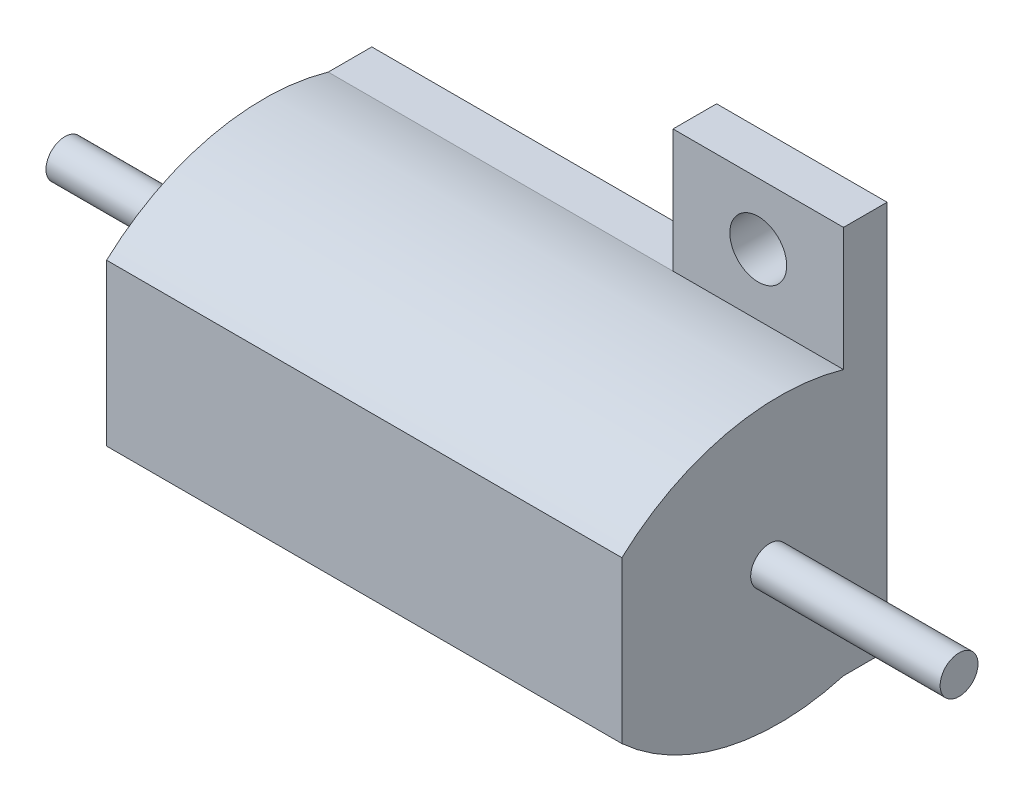
SolidWorks part; units mm, degrees
ref_plane "前视基准面" through (0, 0, 0) normal (0, 0, 1) x (1, 0, 0)
ref_plane "上视基准面" through (0, 0, 0) normal (0, 1, 0) x (1, 0, 0)
ref_plane "右视基准面" through (0, 0, 0) normal (1, 0, 0) x (0, 0, -1)
sketch "草图1" plane through (0, 0, 0) normal (0, 0, 1) x (1, 0, 0)
  line L0 (0, 21.2759) -> (0, -16.314) construction
  line L1 (-13.6, 7) -> (13.6, 7)
  line L2 (-13.6, 7) -> (-13.6, -7)
  line L3 (-13.6, -7) -> (13.6, -7)
  line L4 (13.6, 7) -> (13.6, -7)
  line L5 (-25.4038, 0) -> (20.5157, 0) construction
  dimension "D1" = 27.2
  dimension "D2" = 14
extrude "拉伸1" add sketch "草图1" along normal blind 2.3
sketch "草图2" plane through (0, 0, 0) normal (0, 0, -1) x (-1, 0, 0)
  line L0 (-9.1, 19.1659) -> (-9.1, 5.2783) construction
  line L1 (13.6, -7) -> (4.6, -7)
  line L2 (13.6, -7) -> (13.6, -13.5)
  line L3 (13.6, -13.5) -> (4.6, -13.5)
  line L4 (4.6, -7) -> (4.6, -13.5)
  line L5 (-13.6, 7) -> (-4.6, 7)
  line L6 (-13.6, 7) -> (-13.6, 13.5)
  line L7 (-13.6, 13.5) -> (-4.6, 13.5)
  line L8 (-4.6, 7) -> (-4.6, 13.5)
  line L9 (-1.9119, 10.25) -> (-15.2555, 10.25) construction
  line L10 (1.9413, -10.25) -> (18.3757, -10.25) construction
  line L11 (9.1, -6.7597) -> (9.1, -18.109) construction
  circle A0 centre (-9.1, 10.25) radius 1.5
  circle A1 centre (9.1, -10.25) radius 1.5
  dimension "D5" = 3
  dimension "D6" = 3
  dimension "D1" = 6.5
  dimension "D2" = 9
  dimension "D3" = 6.5
  dimension "D4" = 9
extrude "拉伸2" add sketch "草图2" against normal up to surface (2.3 mm away) up to face at (0, 0, 2.3)
sketch "草图4" plane through (13.6, 0, 0) normal (1, 0, 0) x (0, 0, -1)
  line L0 (-2.3, -7) -> (-2.3, 7)
  line L1 (8.3066, 0) -> (-17.5153, 0) construction
  line L2 (-14, -4.25) -> (-14, 4.25)
  line L3 (0, -7) -> (0, 13.5) construction
  arc A0 (-2.3, -7) -> (-14, -4.25) centre (-5.6986, 4.8047) cw
  arc A1 (-2.3, 7) -> (-14, 4.25) centre (-5.6986, -4.8047) ccw
  point P14 (-14, 0)
  dimension "D1" = 14
  dimension "D2" = 8.5
extrude "拉伸3" add sketch "草图4" against normal up to surface (27.2 mm away) up to face at (-13.6, -3.25, 1.15)
sketch "草图5" plane through (0, 0, 0) normal (1, 0, 0) x (0, 0, -1)
  line L0 (2.7647, 0) -> (-20.739, 0) construction
  line L1 (0, -7) -> (0, 13.5) construction
  circle A0 centre (-6.2, 0) radius 1
  dimension "D2" = 2
  dimension "D1" = 6.2
extrude "拉伸4" add sketch "草图5" along normal offset from surface 10 and the other way offset from surface (23.6 mm away) 10 up to face at (13.6, 2.3709, 4.2013) offset beyond the face yes other way up to face at (-13.6, -2.3709, 4.2013)
